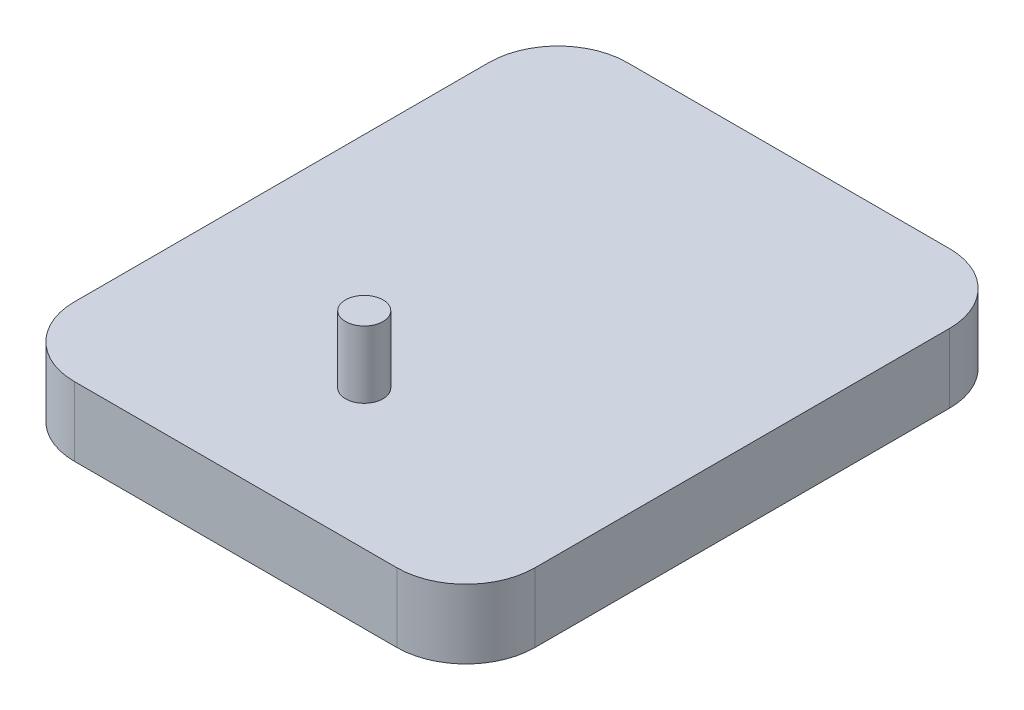
SolidWorks part; units mm, degrees
other "EndMill"
material "Brass"
ref_plane "Front Plane" through (0, 0, 0) normal (0, 0, 1) x (1, 0, 0)
ref_plane "Top Plane" through (0, 0, 0) normal (0, 1, 0) x (1, 0, 0)
ref_plane "Right Plane" through (0, 0, 0) normal (1, 0, 0) x (0, 0, -1)
sketch "Sketch1" plane through (0, 0, 0) normal (0, 1, 0) x (1, 0, 0)
  line L0 (-127, 152.4) -> (127, -152.4) construction
  line L1 (-127, 152.4) -> (127, 152.4)
  line L2 (-127, 152.4) -> (-127, -152.4)
  line L3 (-127, -152.4) -> (127, -152.4)
  line L4 (127, 152.4) -> (127, -152.4)
  dimension "D1" = 254
  dimension "D2" = 304.8
extrude "Boss-Extrude1" add sketch "Sketch1" along normal blind 38.1
fillet "Fillet1" radius 38.1 4 edges at (-127, 19.05, -152.4) (127, 19.05, -152.4) (127, 19.05, 152.4) (-127, 19.05, 152.4)
sketch "Sketch2" plane through (0, 0, 0) normal (0, 0, 1) x (1, 0, 0)
  line L0 (127, 38.1) -> (127, 6.35)
  line L1 (127, 38.1) -> (127, 0) construction
  line L2 (127, 6.35) -> (121.92, 6.35)
  line L3 (121.92, 6.35) -> (121.92, 11.43)
  line L4 (121.92, 11.43) -> (119.38, 11.43)
  line L5 (109.22, 21.59) -> (109.22, 27.94)
  line L6 (109.22, 27.94) -> (104.14, 27.94)
  line L7 (104.14, 27.94) -> (104.14, 31.75)
  line L8 (127, 38.1) -> (88.9, 38.1) construction
  line L9 (97.79, 38.1) -> (127, 38.1)
  line L10 (88.9, 0) -> (127, 0) construction
  arc A0 (119.38, 11.43) -> (109.22, 21.59) centre (119.38, 21.59) cw
  arc A1 (104.14, 31.75) -> (97.79, 38.1) centre (97.79, 31.75) ccw
  dimension "D6" = 6.35
  dimension "D8" = 10.16
  dimension "D1" = 5.08
  dimension "D2" = 6.35
  dimension "D3" = 17.78
  dimension "D4" = 10.16
  dimension "D5" = 22.86
  dimension "D7" = 5.08
sketch "Sketch3" plane through (0, 38.1, 0) normal (0, 1, 0) x (1, 0, 0)
  line L4 (88.9, 152.4) -> (-88.9, 152.4)
  line L5 (-127, 114.3) -> (-127, -114.3)
  line L6 (-88.9, -152.4) -> (88.9, -152.4)
  line L7 (127, -114.3) -> (127, 114.3)
  line L8 (88.9, 152.4) -> (-88.9, 152.4)
  line L9 (-127, 114.3) -> (-127, -114.3)
  line L10 (-88.9, -152.4) -> (88.9, -152.4)
  line L11 (127, -114.3) -> (127, 114.3)
  arc A4 (-88.9, 152.4) -> (-127, 114.3) centre (-88.9, 114.3) ccw
  arc A5 (-127, -114.3) -> (-88.9, -152.4) centre (-88.9, -114.3) ccw
  arc A6 (88.9, -152.4) -> (127, -114.3) centre (88.9, -114.3) ccw
  arc A7 (127, 114.3) -> (88.9, 152.4) centre (88.9, 114.3) ccw
  arc A8 (-88.9, 152.4) -> (-127, 114.3) centre (-88.9, 114.3) ccw
  arc A9 (-127, -114.3) -> (-88.9, -152.4) centre (-88.9, -114.3) ccw
  arc A10 (88.9, -152.4) -> (127, -114.3) centre (88.9, -114.3) ccw
  arc A11 (127, 114.3) -> (88.9, 152.4) centre (88.9, 114.3) ccw
  dimension "D1" = 0
sketch "Sketch4" plane through (0, 0, 0) normal (1, 0, 0) x (0, 0, -1)
  line L1 (-91.8301, 80.9453) -> (-81.4767, 80.9453)
  line L2 (-91.8301, 80.9453) -> (-91.8301, 44.0332)
  line L3 (-91.8301, 44.0332) -> (-81.4767, 44.0332)
  line L4 (-81.4767, 80.9453) -> (-81.4767, 44.0332)
revolve "Revolve1" add sketch "Sketch4" angle 360 about L4
sketch "Sketch5" plane through (0, 0, 0) normal (1, 0, 0) x (0, 0, -1)
  line L0 (-81.4767, 44.0332) -> (28.8135, 14.7299)
  line L1 (-91.8301, 44.0332) -> (-71.1233, 44.0332) construction
